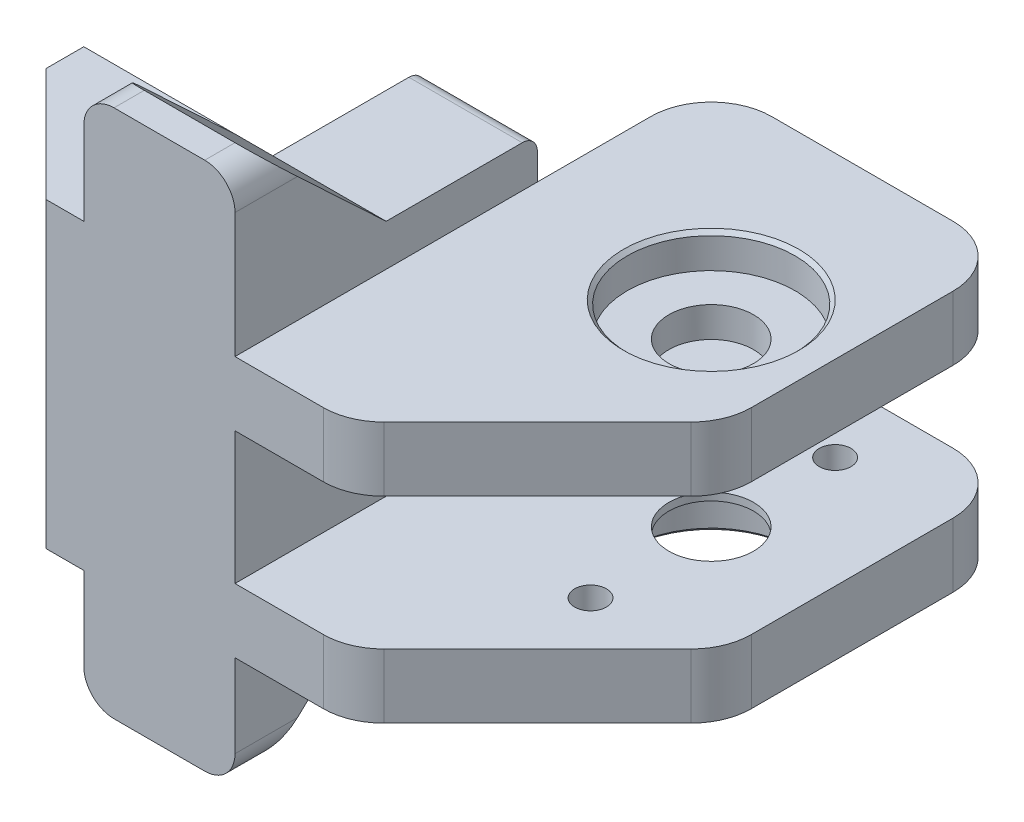
SolidWorks part; units mm, degrees
ref_plane "Front Plane" through (0, 0, 0) normal (0, 0, 1) x (1, 0, 0)
ref_plane "Top Plane" through (0, 0, 0) normal (0, 1, 0) x (1, 0, 0)
ref_plane "Right Plane" through (0, 0, 0) normal (1, 0, 0) x (0, 0, -1)
sketch "Sketch1" plane through (0, 0, 0) normal (0, 1, 0) x (1, 0, 0)
  line L1 (0, 0) -> (40, 0)
  line L2 (0, 0) -> (0, 40)
  line L3 (0, 40) -> (40, 40)
  line L4 (40, 0) -> (40, 40)
extrude "Boss-Extrude1" add sketch "Sketch1" along normal blind 40
sketch "Sketch2" plane through (0, 40, 0) normal (0, 1, 0) x (1, 0, 0)
  line L0 (0, 40) -> (25, 40)
  line L1 (40, 40) -> (0, 40) construction
  line L2 (25, 40) -> (25, 20)
  line L3 (25, 20) -> (0, 20)
  line L4 (0, 40) -> (0, 0) construction
  line L5 (0, 20) -> (0, 40)
extrude "Cut-Extrude1" cut sketch "Sketch2" against normal blind 40
chamfer "Chamfer1" distance 15 angle 45 1 edges at (0, 20, 0)
sketch "Sketch3" plane through (0, 0, 0) normal (0, 0, 1) x (1, 0, 0)
  line L4 (0, 0) -> (0, 40) construction
  line L5 (0, 10) -> (0, 15)
  line L6 (0, 15) -> (15, 15)
  line L7 (15, 15) -> (15, 5)
  line L8 (15, 5) -> (0, 5)
  line L9 (0, 5) -> (0, 10)
  line L11 (0, 30) -> (0, 25)
  line L12 (0, 25) -> (15, 25)
  line L13 (15, 25) -> (15, 35)
  line L14 (15, 35) -> (0, 35)
  line L15 (0, 35) -> (0, 30)
extrude "Cut-Extrude2" cut sketch "Sketch3" against normal blind 15
chamfer "Chamfer2" distance 4 angle 45 4 edges at (15, 5, -7.5) (15, 15, -7.5) (15, 35, -7.5) (15, 25, -7.5)
sketch "Sketch4" plane through (0, 0, -15) normal (0, 0, 1) x (1, 0, 0)
  line L0 (0, 30) -> (8, 30)
  line L1 (0, 35) -> (0, 25) construction
  line L2 (0, 10) -> (8, 10)
  line L3 (0, 15) -> (0, 5) construction
  circle A0 centre (8, 30) radius 2.6
  circle A1 centre (8, 10) radius 2.6
extrude "Cut-Extrude3" cut sketch "Sketch4" against normal blind 17
sketch "Sketch5" plane through (0, 0, -40) normal (0, 0, -1) x (-1, 0, 0)
  line L0 (-40, 20) -> (-85, 20) construction
  line L1 (-40, 40) -> (-40, 0) construction
  line L5 (-80, 8.5) -> (-40, 8.5)
  line L11 (-40, 20) -> (-40, 26)
  line L12 (-40, 40) -> (-40, 0) construction
  line L13 (-40, 26) -> (-80, 26)
  line L14 (-40, 26) -> (-40, 34.5)
  line L15 (-40, 34.5) -> (-80, 34.5)
  line L16 (-80, 34.5) -> (-80, 26)
  line L17 (-40, 8.5) -> (-40, 0)
  line L18 (-40, 0) -> (-80, 0)
  line L19 (-80, 0) -> (-80, 8.5)
  dimension "D1" = 11.5
  dimension "D2" = 6
  dimension "8" = 8.5
extrude "Boss-Extrude2" add sketch "Sketch5" along normal blind 8 and the other way blind 40
sketch "Sketch10" plane through (40, 0, 0) normal (1, 0, 0) x (0, 0, -1)
  line L0 (40, 20) -> (36, 20)
  line L1 (40, 25) -> (40, 15) construction
  line L2 (36, 15) -> (36, 25)
  line L3 (40, 25) -> (0, 25) construction
  line L4 (36, 25) -> (22, 25)
  line L5 (22, 25) -> (22, 15)
  line L6 (36, 15) -> (22, 15)
  point P10 (22, 20)
  dimension "D1" = 4
  dimension "D2" = 14
extrude "Cut-Extrude5" cut sketch "Sketch10" against normal blind 26
sketch "Sketch8" plane through (0, 32, 0) normal (0, 1, 0) x (1, 0, 0)
  line L0 (80, 48) -> (80, 38) construction
  line L2 (80, 48) -> (80, 0) construction
  line L3 (80, 38) -> (65, 38) construction
  circle A1 centre (65, 38) radius 5.6
extrude "Cut-Extrude4" cut sketch "Sketch8" against normal blind 34
sketch "Sketch9" plane through (40, 0, 0) normal (1, 0, 0) x (0, 0, -1)
  line L0 (0, 40) -> (0, 55)
  line L1 (0, 40) -> (20, 40)
  line L2 (0, 40) -> (40, 40) construction
  line L4 (0, 0) -> (0, -15)
  line L5 (0, 0) -> (20, 0)
  line L7 (0, 55) -> (4, 55)
  line L8 (4, 55) -> (20, 40)
  line L9 (0, -15) -> (4, -15)
  line L10 (4, -15) -> (20, 0)
extrude "Boss-Extrude3" add sketch "Sketch9" against normal blind 20
fillet "Fillet3" radius 4 4 edges at (20, -15, -2) (40, -15, -2) (20, 55, -2) (40, 55, -2)
fillet "Fillet4" radius 2 2 edges at (32.5, 0, -40) (32.5, 40, -40)
chamfer "Chamfer7" distance 25 angle 45 2 edges at (80, 4.25, 0) (80, 30.25, 0)
chamfer "Chamfer8" distance 2 distance2 10 1 edges at (40, 20, -36)
fillet "Fillet7" radius 2 6 edges at (27.5, 25, -36) (27.5, 15, -36) (32.5, 15, -22) (32.5, 25, -22) (35, 25, -37) (35, 15, -37)
sketch "Sketch14" plane through (0, 0, -48) normal (0, 0, -1) x (-1, 0, 0)
  line L0 (-80, 8.5) -> (-40, 8.5)
  line L1 (-80, 8.5) -> (-40, 8.5) construction
  line L2 (-40, 8.5) -> (-40, 0)
  line L3 (-40, 0) -> (-80, 0)
  line L4 (-80, 0) -> (-80, 8.5)
extrude "Boss-Extrude4" add sketch "Sketch14" along normal blind 15
sketch "Sketch16" plane through (0, 0, -48) normal (0, 0, -1) x (-1, 0, 0)
  line L0 (-80, 26) -> (-80, 34.5)
  line L1 (-80, 34.5) -> (-40, 34.5)
  line L2 (-40, 34.5) -> (-40, 26)
  line L3 (-40, 26) -> (-80, 26)
extrude "Boss-Extrude5" add sketch "Sketch16" along normal up to surface (15 mm away) up to face at (60, 4.25, -63)
sketch "Sketch12" plane through (0, 34.5, 0) normal (0, 1, 0) x (1, 0, 0)
  circle A1 centre (65, 38) radius 11.1
extrude "Cut-Extrude6" cut sketch "Sketch12" against normal blind 4.5
sketch "Sketch13" plane through (0, 0, 0) normal (0, -1, 0) x (1, 0, 0)
  circle A1 centre (65, -38) radius 11.1
extrude "Cut-Extrude7" cut sketch "Sketch13" against normal blind 7.5
sketch "Sketch15" plane through (0, 0, 0) normal (0, -1, 0) x (1, 0, 0)
  circle A0 centre (65.2609, -54.1305) radius 2.1
  circle A1 centre (65.169, -21.8682) radius 2.1
extrude "Cut-Extrude8" cut sketch "Sketch15" against normal blind 10
chamfer "Chamfer10" distance 0.5 angle 45 2 edges at (53.9, 34.5, -38) (65, 0, -49.1)
fillet "Fillet8" radius 8 8 edges at (40, 4.25, -63) (80, 4.25, -63) (55, 4.25, 0) (55, 30.25, 0) (80, 30.25, -25) (80, 4.25, -25) (40, 30.25, -63) (80, 30.25, -63)
